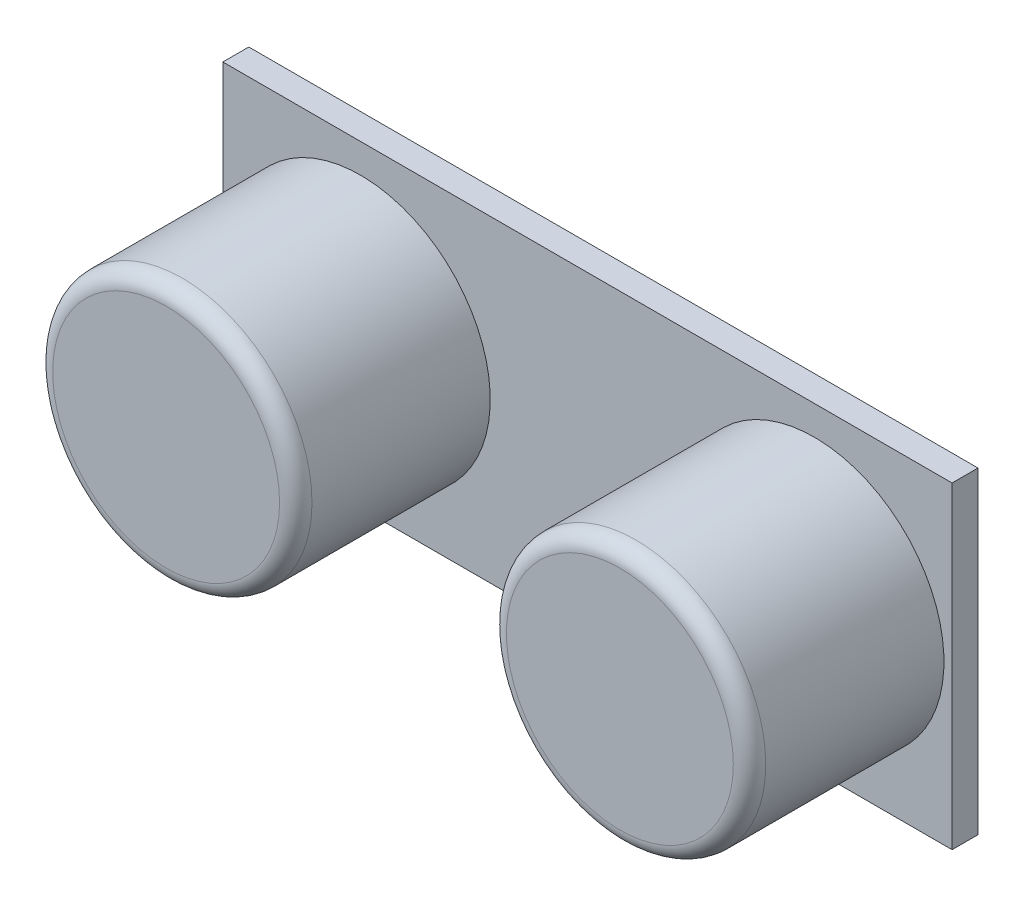
SolidWorks part; units mm, degrees
ref_plane "Front Plane" through (0, 0, 0) normal (0, 0, 1) x (1, 0, 0)
ref_plane "Top Plane" through (0, 0, 0) normal (0, 1, 0) x (1, 0, 0)
ref_plane "Right Plane" through (0, 0, 0) normal (1, 0, 0) x (0, 0, -1)
sketch "草图1" plane through (0, 0, 0) normal (0, 0, 1) x (1, 0, 0)
  line L1 (0, 0) -> (45, 0)
  line L2 (0, 0) -> (0, 19.6)
  line L3 (0, 19.6) -> (45, 19.6)
  line L4 (45, 0) -> (45, 19.6)
  dimension "D1" = 45
  dimension "D2" = 19.6
extrude "凸台-拉伸1" add sketch "草图1" along normal blind 1.6
sketch "草图2" plane through (0, 0, 1.6) normal (0, 0, 1) x (1, 0, 0)
  line L0 (0, 19.6) -> (0, 0) construction
  line L1 (0, 9.8) -> (45, 9.8) construction
  line L2 (45, 0) -> (45, 19.6) construction
  circle A0 centre (8.5, 9.8) radius 8
  circle A1 centre (36.5, 9.8) radius 8
  dimension "D2" = 16
  dimension "D4" = 16
  dimension "D1" = 8.5
  dimension "D3" = 8.5
extrude "凸台-拉伸2" add sketch "草图2" along normal blind 12
fillet "圆角1" radius 1 2 edges at (44.5, 9.8, 13.6) (16.5, 9.8, 13.6)
